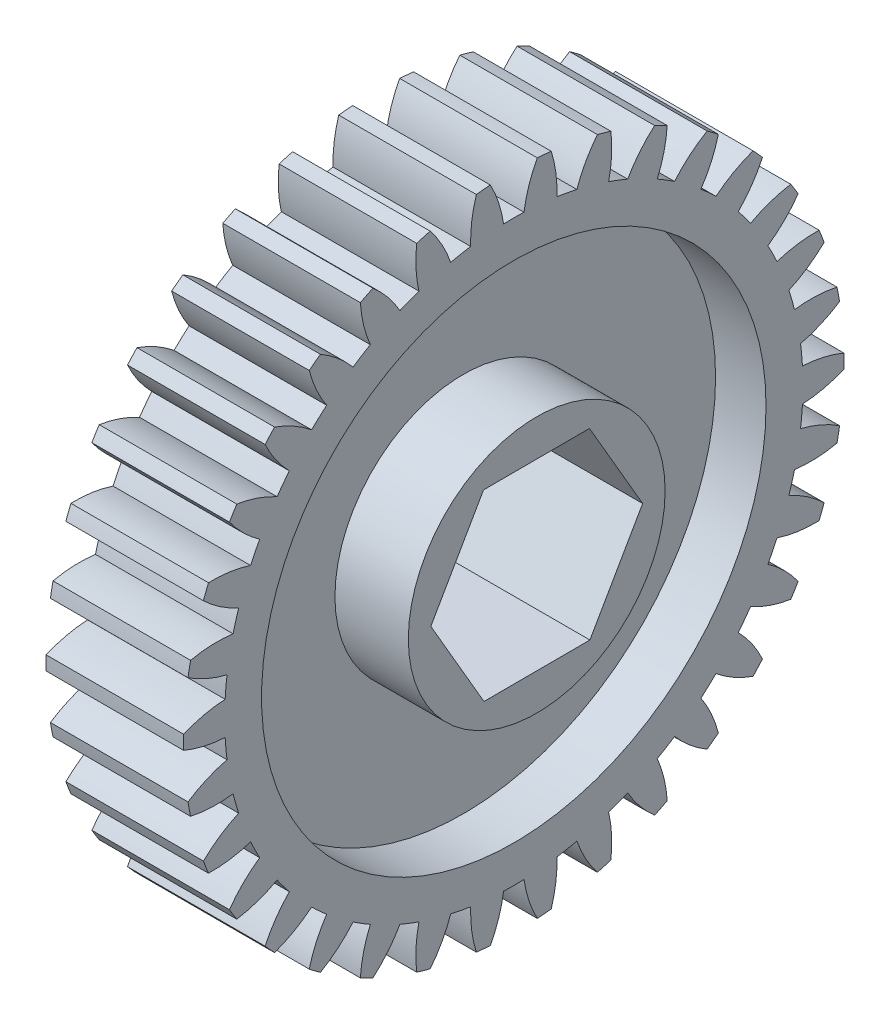
SolidWorks part; units mm, degrees
ref_plane "Front Plane" through (0, 0, 0) normal (0, 0, 1) x (1, 0, 0)
ref_plane "Top Plane" through (0, 0, 0) normal (0, 1, 0) x (1, 0, 0)
ref_plane "Right Plane" through (0, 0, 0) normal (1, 0, 0) x (0, 0, -1)
ref_plane "Plane1" through (0, 0, 0) normal (0, 0, -1) x (-1, 0, 0)
sketch "Sketch1" plane through (0, 0, 0) normal (0, 0, -1) x (-1, 0, 0)
  line L0 (-9.525, 22.86) -> (-9.525, 0)
  line L1 (-9.525, 0) -> (0, 0)
  line L2 (0, 0) -> (0, 22.86)
  line L3 (0, 22.86) -> (-9.525, 22.86)
  line L4 (-9.525, 0) -> (0, 0) construction
revolve "Revolve1" add sketch "Sketch1" angle 360 about L4
sketch "Sketch2" plane through (0, 0, 0) normal (-1, 0, 0) x (0, 0, 1)
  arc A0 (-2.5918, 22.7126) -> (-5.788, 22.1151) centre (0, 0) ccw
  arc A1 (-5.788, 22.1151) -> (-4.3689, 19.5326) centre (-12.5361, 16.7258) cw
  arc A2 (-4.3689, 19.5326) -> (-2.9821, 19.7918) centre (0, 0) cw
  arc A3 (-2.9821, 19.7918) -> (-2.5918, 22.7126) centre (5.6474, 20.1249) cw
extrude "Cut-Extrude1" cut sketch "Sketch2" against normal through all
sketch "Sketch3" plane through (0, 0, 0) normal (-1, 0, 0) x (0, 0, 1)
  arc A0 (1.6258, 22.8021) -> (-1.6258, 22.8021) centre (0, 0) ccw
  arc A1 (-1.6258, 22.8021) -> (-0.7054, 20.0028) centre (-9.2492, 18.7445) cw
  arc A2 (-0.7054, 20.0028) -> (0.7054, 20.0028) centre (0, 0) cw
  arc A3 (0.7054, 20.0028) -> (1.6258, 22.8021) centre (9.2492, 18.7445) cw
extrude "Cut-Extrude2" cut sketch "Sketch3" against normal through all
sketch "Sketch4" plane through (0, 0, 0) normal (-1, 0, 0) x (0, 0, 1)
  arc A0 (5.788, 22.1151) -> (2.5918, 22.7126) centre (0, 0) ccw
  arc A1 (2.5918, 22.7126) -> (2.9821, 19.7918) centre (-5.6474, 20.1249) cw
  arc A2 (2.9821, 19.7918) -> (4.3689, 19.5326) centre (0, 0) cw
  arc A3 (4.3689, 19.5326) -> (5.788, 22.1151) centre (12.5361, 16.7258) cw
extrude "Cut-Extrude3" cut sketch "Sketch4" against normal through all
sketch "Sketch5" plane through (0, 0, 0) normal (-1, 0, 0) x (0, 0, 1)
  arc A0 (9.7531, 20.675) -> (6.7211, 21.8496) centre (0, 0) ccw
  arc A1 (6.7211, 21.8496) -> (6.5681, 18.9068) centre (-1.8533, 20.82) cw
  arc A2 (6.5681, 18.9068) -> (7.8836, 18.3972) centre (0, 0) cw
  arc A3 (7.8836, 18.3972) -> (9.7531, 20.675) centre (15.396, 14.1376) cw
extrude "Cut-Extrude4" cut sketch "Sketch5" against normal through all
sketch "Sketch6" plane through (0, 0, 0) normal (-1, 0, 0) x (0, 0, 1)
  arc A0 (13.3861, 18.5309) -> (10.6215, 20.2426) centre (0, 0) ccw
  arc A1 (10.6215, 20.2426) -> (9.9304, 17.378) centre (2.0039, 20.806) cw
  arc A2 (9.9304, 17.378) -> (11.1298, 16.6354) centre (0, 0) cw
  arc A3 (11.1298, 16.6354) -> (13.3861, 18.5309) centre (17.7316, 11.0678) cw
extrude "Cut-Extrude5" cut sketch "Sketch6" against normal through all
sketch "Sketch7" plane through (0, 0, 0) normal (-1, 0, 0) x (0, 0, 1)
  arc A0 (16.5632, 15.7557) -> (14.1602, 17.9463) centre (0, 0) ccw
  arc A1 (14.1602, 17.9463) -> (12.9545, 15.2574) centre (5.7929, 20.0836) cw
  arc A2 (12.9545, 15.2574) -> (13.9971, 14.307) centre (0, 0) cw
  arc A3 (13.9971, 14.307) -> (16.5632, 15.7557) centre (19.4634, 7.6212) cw
extrude "Cut-Extrude6" cut sketch "Sketch7" against normal through all
sketch "Sketch8" plane through (0, 0, 0) normal (-1, 0, 0) x (0, 0, 1)
  arc A0 (19.1762, 12.4439) -> (17.2167, 15.0388) centre (0, 0) ccw
  arc A1 (17.2167, 15.0388) -> (15.5375, 12.6173) centre (9.3846, 18.6772) cw
  arc A2 (15.5375, 12.6173) -> (16.3876, 11.4915) centre (0, 0) cw
  arc A3 (16.3876, 11.4915) -> (19.1762, 12.4439) centre (20.5324, 3.9151) cw
extrude "Cut-Extrude7" cut sketch "Sketch8" against normal through all
sketch "Sketch9" plane through (0, 0, 0) normal (-1, 0, 0) x (0, 0, 1)
  arc A0 (21.1363, 8.7084) -> (19.6869, 11.6191) centre (0, 0) ccw
  arc A1 (19.6869, 11.6191) -> (17.5913, 9.5474) centre (12.6567, 16.6347) cw
  arc A2 (17.5913, 9.5474) -> (18.2202, 8.2846) centre (0, 0) cw
  arc A3 (18.2202, 8.2846) -> (21.1363, 8.7084) centre (20.9022, 0.0756) cw
extrude "Cut-Extrude8" cut sketch "Sketch9" against normal through all
sketch "Sketch10" plane through (0, 0, 0) normal (-1, 0, 0) x (0, 0, 1)
  arc A0 (22.3766, 4.6764) -> (21.4867, 7.8038) centre (0, 0) ccw
  arc A1 (21.4867, 7.8038) -> (19.0461, 6.1525) centre (15.4978, 14.0258) cw
  arc A2 (19.0461, 6.1525) -> (19.4322, 4.7956) centre (0, 0) cw
  arc A3 (19.4322, 4.7956) -> (22.3766, 4.6764) centre (20.5602, -3.7665) cw
extrude "Cut-Extrude9" cut sketch "Sketch10" against normal through all
sketch "Sketch11" plane through (0, 0, 0) normal (-1, 0, 0) x (0, 0, 1)
  arc A0 (22.8549, 0.485) -> (22.5548, 3.7228) centre (0, 0) ccw
  arc A1 (22.5548, 3.7228) -> (19.8524, 2.548) centre (17.8112, 10.9393) cw
  arc A2 (19.8524, 2.548) -> (19.9825, 1.1432) centre (0, 0) cw
  arc A3 (19.9825, 1.1432) -> (22.8549, 0.485) centre (19.518, -7.4803) cw
extrude "Cut-Extrude10" cut sketch "Sketch11" against normal through all
sketch "Sketch12" plane through (0, 0, 0) normal (-1, 0, 0) x (0, 0, 1)
  arc A0 (22.5548, -3.7228) -> (22.8549, -0.485) centre (0, 0) ccw
  arc A1 (22.8549, -0.485) -> (19.9825, -1.1432) centre (19.518, 7.4803) cw
  arc A2 (19.9825, -1.1432) -> (19.8524, -2.548) centre (0, 0) cw
  arc A3 (19.8524, -2.548) -> (22.5548, -3.7228) centre (17.8112, -10.9393) cw
extrude "Cut-Extrude11" cut sketch "Sketch12" against normal through all
sketch "Sketch13" plane through (0, 0, 0) normal (-1, 0, 0) x (0, 0, 1)
  arc A0 (21.4867, -7.8038) -> (22.3766, -4.6764) centre (0, 0) ccw
  arc A1 (22.3766, -4.6764) -> (19.4322, -4.7956) centre (20.5602, 3.7665) cw
  arc A2 (19.4322, -4.7956) -> (19.0461, -6.1525) centre (0, 0) cw
  arc A3 (19.0461, -6.1525) -> (21.4867, -7.8038) centre (15.4978, -14.0258) cw
extrude "Cut-Extrude12" cut sketch "Sketch13" against normal through all
sketch "Sketch14" plane through (0, 0, 0) normal (-1, 0, 0) x (0, 0, 1)
  arc A0 (19.6869, -11.6191) -> (21.1363, -8.7084) centre (0, 0) ccw
  arc A1 (21.1363, -8.7084) -> (18.2202, -8.2846) centre (20.9022, -0.0756) cw
  arc A2 (18.2202, -8.2846) -> (17.5913, -9.5474) centre (0, 0) cw
  arc A3 (17.5913, -9.5474) -> (19.6869, -11.6191) centre (12.6567, -16.6347) cw
extrude "Cut-Extrude13" cut sketch "Sketch14" against normal through all
sketch "Sketch15" plane through (0, 0, 0) normal (-1, 0, 0) x (0, 0, 1)
  arc A0 (17.2167, -15.0388) -> (19.1762, -12.4439) centre (0, 0) ccw
  arc A1 (19.1762, -12.4439) -> (16.3876, -11.4915) centre (20.5324, -3.9151) cw
  arc A2 (16.3876, -11.4915) -> (15.5375, -12.6173) centre (0, 0) cw
  arc A3 (15.5375, -12.6173) -> (17.2167, -15.0388) centre (9.3846, -18.6772) cw
extrude "Cut-Extrude14" cut sketch "Sketch15" against normal through all
sketch "Sketch16" plane through (0, 0, 0) normal (-1, 0, 0) x (0, 0, 1)
  arc A0 (14.1602, -17.9463) -> (16.5632, -15.7557) centre (0, 0) ccw
  arc A1 (16.5632, -15.7557) -> (13.9971, -14.307) centre (19.4634, -7.6212) cw
  arc A2 (13.9971, -14.307) -> (12.9545, -15.2574) centre (0, 0) cw
  arc A3 (12.9545, -15.2574) -> (14.1602, -17.9463) centre (5.7929, -20.0836) cw
extrude "Cut-Extrude15" cut sketch "Sketch16" against normal through all
sketch "Sketch17" plane through (0, 0, 0) normal (-1, 0, 0) x (0, 0, 1)
  arc A0 (10.6215, -20.2426) -> (13.3861, -18.5309) centre (0, 0) ccw
  arc A1 (13.3861, -18.5309) -> (11.1298, -16.6354) centre (17.7316, -11.0678) cw
  arc A2 (11.1298, -16.6354) -> (9.9304, -17.378) centre (0, 0) cw
  arc A3 (9.9304, -17.378) -> (10.6215, -20.2426) centre (2.0039, -20.806) cw
extrude "Cut-Extrude16" cut sketch "Sketch17" against normal through all
sketch "Sketch18" plane through (0, 0, 0) normal (-1, 0, 0) x (0, 0, 1)
  arc A0 (6.7211, -21.8496) -> (9.7531, -20.675) centre (0, 0) ccw
  arc A1 (9.7531, -20.675) -> (7.8836, -18.3972) centre (15.396, -14.1376) cw
  arc A2 (7.8836, -18.3972) -> (6.5681, -18.9068) centre (0, 0) cw
  arc A3 (6.5681, -18.9068) -> (6.7211, -21.8496) centre (-1.8533, -20.82) cw
extrude "Cut-Extrude17" cut sketch "Sketch18" against normal through all
sketch "Sketch19" plane through (0, 0, 0) normal (-1, 0, 0) x (0, 0, 1)
  arc A0 (2.5918, -22.7126) -> (5.788, -22.1151) centre (0, 0) ccw
  arc A1 (5.788, -22.1151) -> (4.3689, -19.5326) centre (12.5361, -16.7258) cw
  arc A2 (4.3689, -19.5326) -> (2.9821, -19.7918) centre (0, 0) cw
  arc A3 (2.9821, -19.7918) -> (2.5918, -22.7126) centre (-5.6474, -20.1249) cw
extrude "Cut-Extrude18" cut sketch "Sketch19" against normal through all
sketch "Sketch20" plane through (0, 0, 0) normal (-1, 0, 0) x (0, 0, 1)
  arc A0 (-1.6258, -22.8021) -> (1.6258, -22.8021) centre (0, 0) ccw
  arc A1 (1.6258, -22.8021) -> (0.7054, -20.0028) centre (9.2492, -18.7445) cw
  arc A2 (0.7054, -20.0028) -> (-0.7054, -20.0028) centre (0, 0) cw
  arc A3 (-0.7054, -20.0028) -> (-1.6258, -22.8021) centre (-9.2492, -18.7445) cw
extrude "Cut-Extrude19" cut sketch "Sketch20" against normal through all
sketch "Sketch21" plane through (0, 0, 0) normal (-1, 0, 0) x (0, 0, 1)
  arc A0 (-5.788, -22.1151) -> (-2.5918, -22.7126) centre (0, 0) ccw
  arc A1 (-2.5918, -22.7126) -> (-2.9821, -19.7918) centre (5.6474, -20.1249) cw
  arc A2 (-2.9821, -19.7918) -> (-4.3689, -19.5326) centre (0, 0) cw
  arc A3 (-4.3689, -19.5326) -> (-5.788, -22.1151) centre (-12.5361, -16.7258) cw
extrude "Cut-Extrude20" cut sketch "Sketch21" against normal through all
sketch "Sketch22" plane through (0, 0, 0) normal (-1, 0, 0) x (0, 0, 1)
  arc A0 (-9.7531, -20.675) -> (-6.7211, -21.8496) centre (0, 0) ccw
  arc A1 (-6.7211, -21.8496) -> (-6.5681, -18.9068) centre (1.8533, -20.82) cw
  arc A2 (-6.5681, -18.9068) -> (-7.8836, -18.3972) centre (0, 0) cw
  arc A3 (-7.8836, -18.3972) -> (-9.7531, -20.675) centre (-15.396, -14.1376) cw
extrude "Cut-Extrude21" cut sketch "Sketch22" against normal through all
sketch "Sketch23" plane through (0, 0, 0) normal (-1, 0, 0) x (0, 0, 1)
  arc A0 (-13.3861, -18.5309) -> (-10.6215, -20.2426) centre (0, 0) ccw
  arc A1 (-10.6215, -20.2426) -> (-9.9304, -17.378) centre (-2.0039, -20.806) cw
  arc A2 (-9.9304, -17.378) -> (-11.1298, -16.6354) centre (0, 0) cw
  arc A3 (-11.1298, -16.6354) -> (-13.3861, -18.5309) centre (-17.7316, -11.0678) cw
extrude "Cut-Extrude22" cut sketch "Sketch23" against normal through all
sketch "Sketch24" plane through (0, 0, 0) normal (-1, 0, 0) x (0, 0, 1)
  arc A0 (-16.5632, -15.7557) -> (-14.1602, -17.9463) centre (0, 0) ccw
  arc A1 (-14.1602, -17.9463) -> (-12.9545, -15.2574) centre (-5.7929, -20.0836) cw
  arc A2 (-12.9545, -15.2574) -> (-13.9971, -14.307) centre (0, 0) cw
  arc A3 (-13.9971, -14.307) -> (-16.5632, -15.7557) centre (-19.4634, -7.6212) cw
extrude "Cut-Extrude23" cut sketch "Sketch24" against normal through all
sketch "Sketch25" plane through (0, 0, 0) normal (-1, 0, 0) x (0, 0, 1)
  arc A0 (-19.1762, -12.4439) -> (-17.2167, -15.0388) centre (0, 0) ccw
  arc A1 (-17.2167, -15.0388) -> (-15.5375, -12.6173) centre (-9.3846, -18.6772) cw
  arc A2 (-15.5375, -12.6173) -> (-16.3876, -11.4915) centre (0, 0) cw
  arc A3 (-16.3876, -11.4915) -> (-19.1762, -12.4439) centre (-20.5324, -3.9151) cw
extrude "Cut-Extrude24" cut sketch "Sketch25" against normal through all
sketch "Sketch26" plane through (0, 0, 0) normal (-1, 0, 0) x (0, 0, 1)
  arc A0 (-21.1363, -8.7084) -> (-19.6869, -11.6191) centre (0, 0) ccw
  arc A1 (-19.6869, -11.6191) -> (-17.5913, -9.5474) centre (-12.6567, -16.6347) cw
  arc A2 (-17.5913, -9.5474) -> (-18.2202, -8.2846) centre (0, 0) cw
  arc A3 (-18.2202, -8.2846) -> (-21.1363, -8.7084) centre (-20.9022, -0.0756) cw
extrude "Cut-Extrude25" cut sketch "Sketch26" against normal through all
sketch "Sketch27" plane through (0, 0, 0) normal (-1, 0, 0) x (0, 0, 1)
  arc A0 (-22.3766, -4.6764) -> (-21.4867, -7.8038) centre (0, 0) ccw
  arc A1 (-21.4867, -7.8038) -> (-19.0461, -6.1525) centre (-15.4978, -14.0258) cw
  arc A2 (-19.0461, -6.1525) -> (-19.4322, -4.7956) centre (0, 0) cw
  arc A3 (-19.4322, -4.7956) -> (-22.3766, -4.6764) centre (-20.5602, 3.7665) cw
extrude "Cut-Extrude26" cut sketch "Sketch27" against normal through all
sketch "Sketch28" plane through (0, 0, 0) normal (-1, 0, 0) x (0, 0, 1)
  arc A0 (-22.8549, -0.485) -> (-22.5548, -3.7228) centre (0, 0) ccw
  arc A1 (-22.5548, -3.7228) -> (-19.8524, -2.548) centre (-17.8112, -10.9393) cw
  arc A2 (-19.8524, -2.548) -> (-19.9825, -1.1432) centre (0, 0) cw
  arc A3 (-19.9825, -1.1432) -> (-22.8549, -0.485) centre (-19.518, 7.4803) cw
extrude "Cut-Extrude27" cut sketch "Sketch28" against normal through all
sketch "Sketch29" plane through (0, 0, 0) normal (-1, 0, 0) x (0, 0, 1)
  arc A0 (-22.5548, 3.7228) -> (-22.8549, 0.485) centre (0, 0) ccw
  arc A1 (-22.8549, 0.485) -> (-19.9825, 1.1432) centre (-19.518, -7.4803) cw
  arc A2 (-19.9825, 1.1432) -> (-19.8524, 2.548) centre (0, 0) cw
  arc A3 (-19.8524, 2.548) -> (-22.5548, 3.7228) centre (-17.8112, 10.9393) cw
extrude "Cut-Extrude28" cut sketch "Sketch29" against normal through all
sketch "Sketch30" plane through (0, 0, 0) normal (-1, 0, 0) x (0, 0, 1)
  arc A0 (-21.4867, 7.8038) -> (-22.3766, 4.6764) centre (0, 0) ccw
  arc A1 (-22.3766, 4.6764) -> (-19.4322, 4.7956) centre (-20.5602, -3.7665) cw
  arc A2 (-19.4322, 4.7956) -> (-19.0461, 6.1525) centre (0, 0) cw
  arc A3 (-19.0461, 6.1525) -> (-21.4867, 7.8038) centre (-15.4978, 14.0258) cw
extrude "Cut-Extrude29" cut sketch "Sketch30" against normal through all
sketch "Sketch31" plane through (0, 0, 0) normal (-1, 0, 0) x (0, 0, 1)
  arc A0 (-19.6869, 11.6191) -> (-21.1363, 8.7084) centre (0, 0) ccw
  arc A1 (-21.1363, 8.7084) -> (-18.2202, 8.2846) centre (-20.9022, 0.0756) cw
  arc A2 (-18.2202, 8.2846) -> (-17.5913, 9.5474) centre (0, 0) cw
  arc A3 (-17.5913, 9.5474) -> (-19.6869, 11.6191) centre (-12.6567, 16.6347) cw
extrude "Cut-Extrude30" cut sketch "Sketch31" against normal through all
sketch "Sketch32" plane through (0, 0, 0) normal (-1, 0, 0) x (0, 0, 1)
  arc A0 (-17.2167, 15.0388) -> (-19.1762, 12.4439) centre (0, 0) ccw
  arc A1 (-19.1762, 12.4439) -> (-16.3876, 11.4915) centre (-20.5324, 3.9151) cw
  arc A2 (-16.3876, 11.4915) -> (-15.5375, 12.6173) centre (0, 0) cw
  arc A3 (-15.5375, 12.6173) -> (-17.2167, 15.0388) centre (-9.3846, 18.6772) cw
extrude "Cut-Extrude31" cut sketch "Sketch32" against normal through all
sketch "Sketch33" plane through (0, 0, 0) normal (-1, 0, 0) x (0, 0, 1)
  arc A0 (-14.1602, 17.9463) -> (-16.5632, 15.7557) centre (0, 0) ccw
  arc A1 (-16.5632, 15.7557) -> (-13.9971, 14.307) centre (-19.4634, 7.6212) cw
  arc A2 (-13.9971, 14.307) -> (-12.9545, 15.2574) centre (0, 0) cw
  arc A3 (-12.9545, 15.2574) -> (-14.1602, 17.9463) centre (-5.7929, 20.0836) cw
extrude "Cut-Extrude32" cut sketch "Sketch33" against normal through all
sketch "Sketch34" plane through (0, 0, 0) normal (-1, 0, 0) x (0, 0, 1)
  arc A0 (-10.6215, 20.2426) -> (-13.3861, 18.5309) centre (0, 0) ccw
  arc A1 (-13.3861, 18.5309) -> (-11.1298, 16.6354) centre (-17.7316, 11.0678) cw
  arc A2 (-11.1298, 16.6354) -> (-9.9304, 17.378) centre (0, 0) cw
  arc A3 (-9.9304, 17.378) -> (-10.6215, 20.2426) centre (-2.0039, 20.806) cw
extrude "Cut-Extrude33" cut sketch "Sketch34" against normal through all
sketch "Sketch35" plane through (0, 0, 0) normal (-1, 0, 0) x (0, 0, 1)
  arc A0 (-6.7211, 21.8496) -> (-9.7531, 20.675) centre (0, 0) ccw
  arc A1 (-9.7531, 20.675) -> (-7.8836, 18.3972) centre (-15.396, 14.1376) cw
  arc A2 (-7.8836, 18.3972) -> (-6.5681, 18.9068) centre (0, 0) cw
  arc A3 (-6.5681, 18.9068) -> (-6.7211, 21.8496) centre (1.8533, 20.82) cw
extrude "Cut-Extrude34" cut sketch "Sketch35" against normal through all
hole_wizard "Hole1" positions "Sketch37" profile "Sketch36" legacy
sketch "Sketch37" plane through (9.525, 0, 0) normal (1, 0, 0) x (0, 0, -1)
  point P0 (0, 0)
sketch "Sketch36" plane through (9.525, 0, 0) normal (0, 1, 0) x (0, 0, -1)
  line L0 (0, 0) -> (0, 3.4925)
  line L1 (0, 3.4925) -> (17.4625, 3.4925)
  line L2 (17.4625, 3.4925) -> (17.4625, 0)
  line L3 (17.4625, 0) -> (0, 0)
  line L4 (0, 110) -> (0, -10) construction
  dimension "Diameter" = 34.925
  dimension "Depth" = 3.4925
sketch "Sketch38" plane through (6.0325, 0, 0) normal (1, 0, 0) x (0, 0, -1)
  circle A0 centre (0, 0) radius 8.89
  dimension "D1" = 17.78
extrude "Boss-Extrude1" add sketch "Sketch38" along normal blind 5.08
hole_wizard "Hole2" positions "Sketch40" profile "Sketch39" legacy
sketch "Sketch40" plane through (0, 0, 0) normal (-1, 0, 0) x (0, 0, 1)
  point P0 (0, 0)
sketch "Sketch39" plane through (0, 0, 0) normal (0, 1, 0) x (0, 0, 1)
  line L0 (0, 0) -> (0, 3.4925)
  line L1 (0, 3.4925) -> (17.4625, 3.4925)
  line L2 (17.4625, 3.4925) -> (17.4625, 0)
  line L3 (17.4625, 0) -> (0, 0)
  line L4 (0, 110) -> (0, -10) construction
  dimension "Diameter" = 34.925
  dimension "Depth" = 3.4925
sketch "Sketch41" plane through (3.4925, 0, 0) normal (-1, 0, 0) x (0, 0, 1)
  circle A0 centre (0, 0) radius 8.89
  dimension "D1" = 17.78
extrude "Boss-Extrude2" add sketch "Sketch41" along normal blind 5.08
sketch "Sketch42" plane through (-1.5875, 0, 0) normal (-1, 0, 0) x (0, 0, 1)
  line L7 (-3.65, 6.3593) -> (-7.3323, 0.0186)
  line L8 (-7.3323, 0.0186) -> (-3.6823, -6.3407)
  line L9 (-3.6823, -6.3407) -> (3.65, -6.3593)
  line L10 (3.65, -6.3593) -> (7.3323, -0.0186)
  line L11 (7.3323, -0.0186) -> (3.6823, 6.3407)
  line L12 (3.6823, 6.3407) -> (-3.65, 6.3593)
  circle A0 centre (0, 0) radius 6.35 construction
  dimension "D2" = 12.7
extrude "Cut-Extrude35" cut sketch "Sketch42" against normal through all
